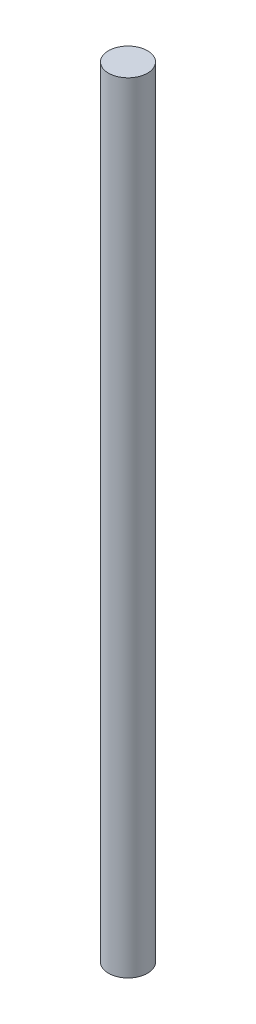
SolidWorks part; units mm, degrees
ref_plane "前视基准面" through (0, 0, 0) normal (0, 0, 1) x (1, 0, 0)
ref_plane "上视基准面" through (0, 0, 0) normal (0, 1, 0) x (1, 0, 0)
ref_plane "右视基准面" through (0, 0, 0) normal (1, 0, 0) x (0, 0, -1)
sketch "草图1" plane through (0, 0, 0) normal (0, 1, 0) x (1, 0, 0)
  circle A0 centre (0, -0.2773) radius 2.5
  dimension "D1" = 5
extrude "凸台-拉伸1" add sketch "草图1" along normal blind 100
